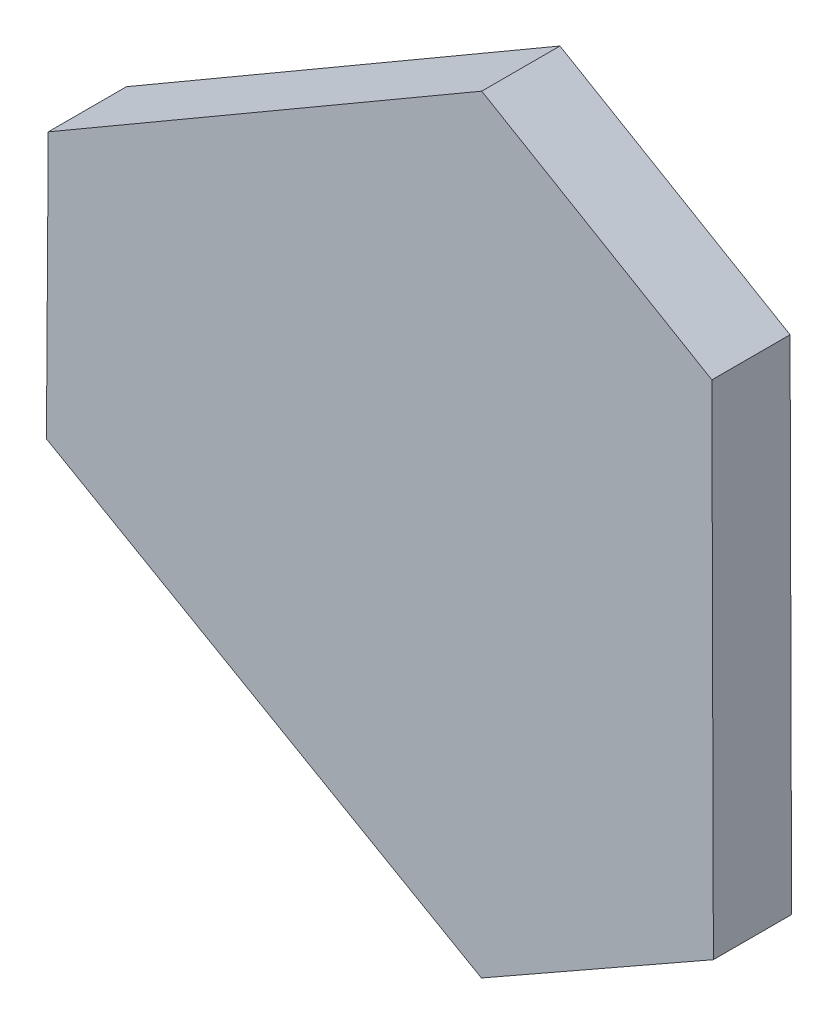
SolidWorks part; units mm, degrees
ref_plane "前视基准面" through (0, 0, 0) normal (0, 0, 1) x (1, 0, 0)
ref_plane "上视基准面" through (0, 0, 0) normal (0, 1, 0) x (1, 0, 0)
ref_plane "右视基准面" through (0, 0, 0) normal (1, 0, 0) x (0, 0, -1)
sketch "草图1" plane through (0, 0, 0) normal (0, 0, 1) x (1, 0, 0)
  line L0 (0, 0) -> (1430.4971, 0) construction
  line L1 (0, 0) -> (762.2528, 639.6061) construction
  line L2 (0, 0) -> (159.3283, 903.5957) construction
  line L3 (0, 0) -> (702.8727, -589.7802) construction
  line L4 (0, 0) -> (172.7887, -979.9333) construction
  line L5 (0, 0) -> (-862.201, -313.8155) construction
  line L6 (0, 0) -> (-935.0415, 340.3273) construction
  line L7 (381.1264, 319.803) -> (383.0222, -321.3938)
  line L8 (383.0222, -321.3938) -> (86.3943, -489.9667)
  line L9 (86.3943, -489.9667) -> (-469.8463, -171.0101)
  line L10 (-469.8463, -171.0101) -> (-467.5208, 170.1636)
  line L11 (-467.5208, 170.1636) -> (86.8241, 492.4039)
  line L12 (86.8241, 492.4039) -> (381.1264, 319.803)
  circle A0 centre (0, 0) radius 500 construction
  point P8 (0, 0)
  point P13 (0, 0)
  dimension "D1" = 80
  dimension "D2" = 40
  dimension "D4" = 3
extrude "凸台-拉伸1" add sketch "草图1" along normal mid plane 100
